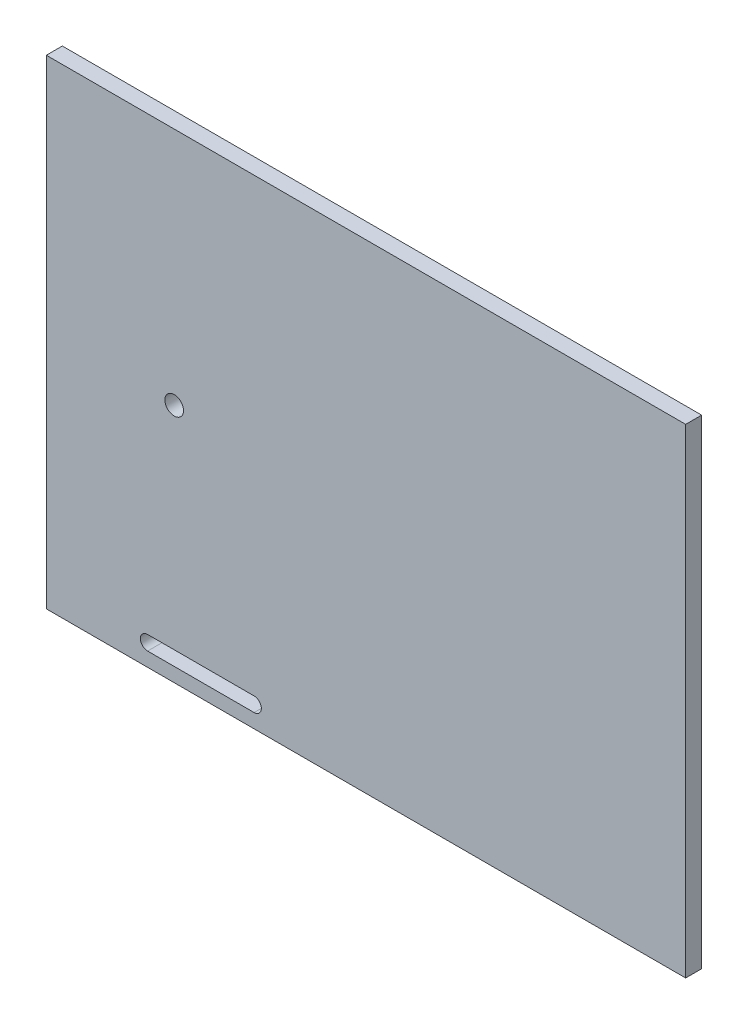
SolidWorks part; units mm, degrees
ref_plane "Front Plane" through (0, 0, 0) normal (0, 0, 1) x (1, 0, 0)
ref_plane "Top Plane" through (0, 0, 0) normal (0, 1, 0) x (1, 0, 0)
ref_plane "Right Plane" through (0, 0, 0) normal (1, 0, 0) x (0, 0, -1)
sketch "Sketch1" plane through (0, 0, 0) normal (0, 0, 1) x (1, 0, 0)
  line L0 (4, -3) -> (4, -74) construction
  line L1 (0, 0) -> (120, 0)
  line L2 (0, 0) -> (0, -90)
  line L3 (0, -90) -> (120, -90)
  line L4 (120, 0) -> (120, -90)
  line L5 (4, -3) -> (0, -3) construction
  line L6 (4, -3) -> (4, 0) construction
  line L7 (60, 0) -> (60, -90) construction
  line L8 (116, -3) -> (116, -74) construction
  circle A0 centre (4, -3) radius 1.35 construction
  circle A1 centre (4, -74) radius 1.35 construction
  circle A2 centre (116, -3) radius 1.35 construction
  circle A3 centre (116, -74) radius 1.35 construction
  dimension "D1" = 2.7
  dimension "D2" = 2.7
  dimension "D3" = 71
  dimension "D4" = 4
  dimension "D5" = 3
  dimension "D6" = 120
  dimension "D7" = 90
extrude "Boss-Extrude1" add sketch "Sketch1" along normal blind 3
fillet "Fillet1" [suppressed] radius 3
sketch "Sketch2" plane through (0, 0, 3) normal (0, 0, 1) x (1, 0, 0)
  line L3 (9.2939, -68.4715) -> (9.2939, -55.8832) construction
  line L11 (27.9692, -19.5285) -> (11.2939, -19.5285) construction
  line L12 (0, 0) -> (0, -90) construction
  line L13 (29.9692, -21.5285) -> (29.9692, -34.1168) construction
  line L15 (0, -45) -> (120, -45) construction
  line L16 (120, 0) -> (120, -90) construction
  line L17 (27.9692, -36.1168) -> (11.2939, -36.1168) construction
  line L28 (39.9401, -54.9529) -> (112.1925, -54.9529) construction
  line L29 (39.9401, -6.9393) -> (112.1925, -6.9393) construction
  line L30 (37.9401, -8.9393) -> (37.9401, -33.0471) construction
  line L31 (39.9401, -35.0471) -> (112.1925, -35.0471) construction
  line L32 (114.1925, -8.9393) -> (114.1925, -33.0471) construction
  line L33 (114.1925, -81.0607) -> (114.1925, -56.9529) construction
  line L34 (39.9401, -83.0607) -> (112.1925, -83.0607) construction
  line L35 (37.9401, -81.0607) -> (37.9401, -56.9529) construction
  line L36 (9.2939, -21.5285) -> (9.2939, -34.1168) construction
  line L37 (27.9692, -53.8832) -> (11.2939, -53.8832) construction
  line L38 (29.9692, -68.4715) -> (29.9692, -55.8832) construction
  line L39 (27.9692, -70.4715) -> (11.2939, -70.4715) construction
  arc A20 (37.9401, -33.0471) -> (39.9401, -35.0471) centre (39.9401, -33.0471) ccw construction
  arc A21 (112.1925, -35.0471) -> (114.1925, -33.0471) centre (112.1925, -33.0471) ccw construction
  arc A22 (112.1925, -6.9393) -> (114.1925, -8.9393) centre (112.1925, -8.9393) cw construction
  arc A23 (39.9401, -6.9393) -> (37.9401, -8.9393) centre (39.9401, -8.9393) ccw construction
  arc A24 (112.1925, -54.9529) -> (114.1925, -56.9529) centre (112.1925, -56.9529) cw construction
  arc A25 (112.1925, -83.0607) -> (114.1925, -81.0607) centre (112.1925, -81.0607) ccw construction
  arc A26 (37.9401, -56.9529) -> (39.9401, -54.9529) centre (39.9401, -56.9529) cw construction
  arc A27 (39.9401, -83.0607) -> (37.9401, -81.0607) centre (39.9401, -81.0607) cw construction
  circle A28 centre (24, -44.9) radius 1.75
  arc A29 (29.9692, -34.1168) -> (27.9692, -36.1168) centre (27.9692, -34.1168) cw construction
  arc A30 (11.2939, -36.1168) -> (9.2939, -34.1168) centre (11.2939, -34.1168) cw construction
  arc A31 (11.2939, -19.5285) -> (9.2939, -21.5285) centre (11.2939, -21.5285) ccw construction
  arc A32 (27.9692, -19.5285) -> (29.9692, -21.5285) centre (27.9692, -21.5285) cw construction
  arc A33 (27.9692, -70.4715) -> (29.9692, -68.4715) centre (27.9692, -68.4715) ccw construction
  arc A34 (11.2939, -70.4715) -> (9.2939, -68.4715) centre (11.2939, -68.4715) cw construction
  arc A35 (11.2939, -53.8832) -> (9.2939, -55.8832) centre (11.2939, -55.8832) ccw construction
  arc A36 (29.9692, -55.8832) -> (27.9692, -53.8832) centre (27.9692, -55.8832) ccw construction
  dimension "D4" = 0.1
  dimension "D5" = 2
  dimension "D1" = 3.5
  dimension "D2" = 2
  dimension "D3" = 24
extrude "Cut-Extrude1" cut sketch "Sketch2" against normal up to surface (3 mm away) up to face at (60, -45, 0)
sketch "Sketch3" plane through (0, 0, 3) normal (0, 0, 1) x (1, 0, 0)
  line L0 (0, -90) -> (120, -90) construction
  line L1 (0, 0) -> (0, -90) construction
  line L2 (19, -86) -> (39, -86) construction
  line L3 (19, -84.65) -> (39, -84.65)
  line L4 (19, -87.35) -> (39, -87.35)
  arc A1 (19, -84.65) -> (19, -87.35) centre (19, -86) ccw
  arc A2 (39, -87.35) -> (39, -84.65) centre (39, -86) ccw
  point P7 (29, -86)
  dimension "D3" = 2.7
  dimension "D1" = 4
  dimension "D2" = 19
  dimension "D4" = 20
extrude "Cut-Extrude2" cut sketch "Sketch3" against normal up to surface (3 mm away) up to face at (25.75, -44.9, 0)
